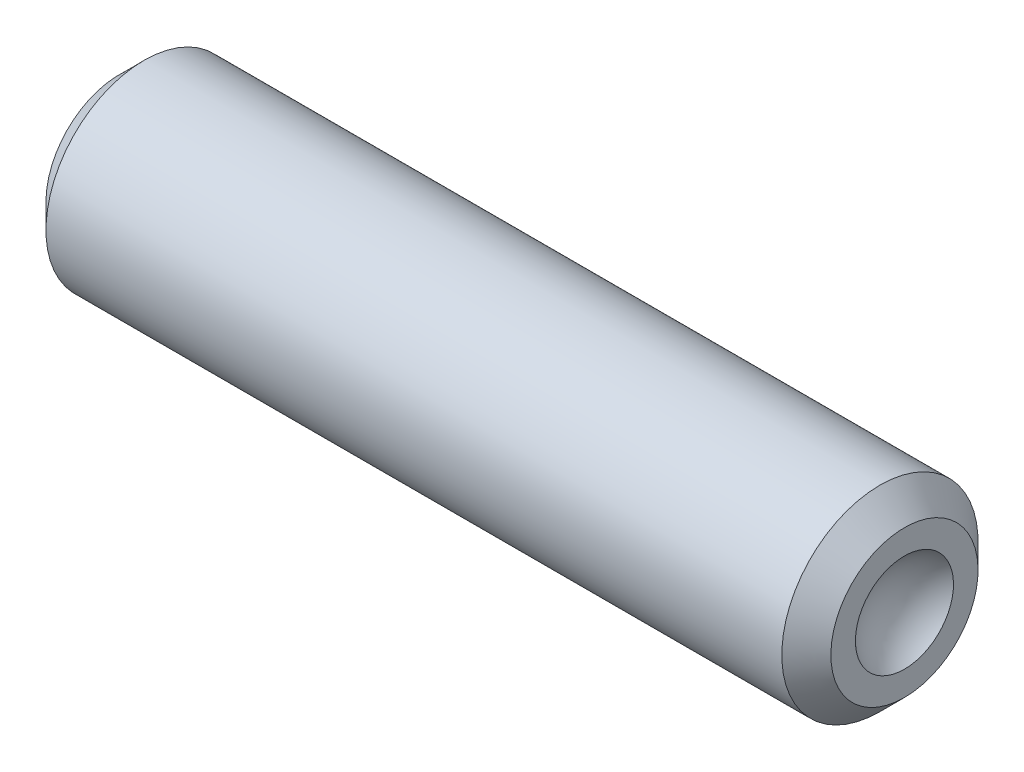
SolidWorks part; units mm, degrees
ref_plane "Front Plane" through (0, 0, 0) normal (0, 0, 1) x (1, 0, 0)
ref_plane "Top Plane" through (0, 0, 0) normal (0, 1, 0) x (1, 0, 0)
ref_plane "Right Plane" through (0, 0, 0) normal (1, 0, 0) x (0, 0, -1)
sketch "Sketch1" plane through (0, 0, 0) normal (0, 0, 1) x (1, 0, 0)
  line L0 (0, 0) -> (0, 1.5)
  line L1 (0, 1.5) -> (0.5, 2)
  line L2 (0.5, 2) -> (15.5, 2)
  line L3 (15.5, 2) -> (16, 1.5)
  line L4 (0, 0) -> (15.5, 0) construction
  line L5 (0.5, 2) -> (0.5, 1.5) construction
  line L6 (0.5, 1.5) -> (0.5, 1) construction
  line L7 (0.5, 1) -> (0.5, 0.5) construction
  line L8 (0.5, 0.5) -> (0.5, 0) construction
  line L9 (0.5, 1.5) -> (0, 1.5) construction
  line L10 (15.5, 2) -> (15.5, 0) construction
  line L11 (16, 1.5) -> (16, 1)
  line L12 (0, 0) -> (15.5, 0)
  arc A0 (15.5, 0) -> (16, 1) centre (16.75, 0) cw
  dimension "D1" = 45
  dimension "D2" = 4
  dimension "D3" = 16
  dimension "D4" = 2
revolve "Revolve1" add sketch "Sketch1" angle 360 about L12
sketch "Sketch2" plane through (0, 0, 0) normal (-1, 0, 0) x (0, 0, 1)
  line L1 (0, 1.1547) -> (-1, 0.5774)
  line L2 (-1, 0.5774) -> (-1, -0.5774)
  line L3 (-1, -0.5774) -> (0, -1.1547)
  line L4 (0, -1.1547) -> (1, -0.5774)
  line L5 (1, -0.5774) -> (1, 0.5774)
  line L6 (1, 0.5774) -> (0, 1.1547)
  circle A0 centre (0, 0) radius 1 construction
  dimension "D1" = 2
extrude "Cut-Extrude1" cut sketch "Sketch2" against normal offset from surface (14 mm away) 2 up to face at (16, -1.5, 0)
